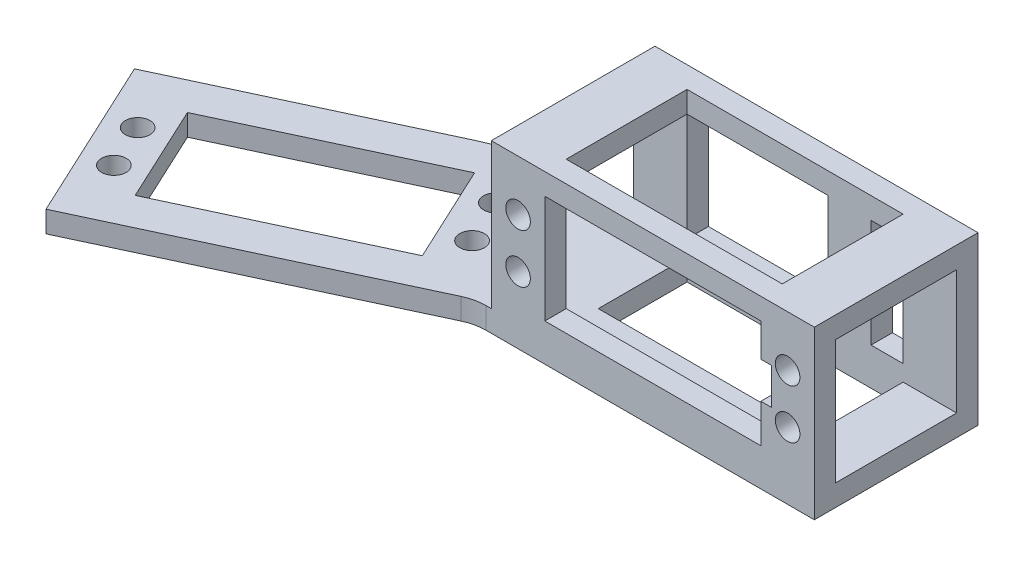
SolidWorks part; units mm, degrees
ref_plane "Płaszczyzna przednia" through (0, 0, 0) normal (0, 0, 1) x (1, 0, 0)
ref_plane "Płaszczyzna górna" through (0, 0, 0) normal (0, 1, 0) x (1, 0, 0)
ref_plane "Płaszczyzna prawa" through (0, 0, 0) normal (1, 0, 0) x (0, 0, -1)
sketch "Szkic1" plane through (0, 0, 0) normal (0, 0, 1) x (1, 0, 0)
  line L0 (17.1567, 10.1) -> (79.0535, 10.1) construction
  line L9 (-10, 27.2) -> (50.4, 27.2)
  line L10 (-10, 27.2) -> (-10, -7)
  line L11 (-10, -7) -> (50.4, -7)
  line L12 (50.4, 27.2) -> (50.4, -7)
  line L13 (20.2, 34.0981) -> (20.2, -18.6436) construction
extrude "Dodanie-wyciągnięcie1" add sketch "Szkic1" along normal blind 4
sketch "Szkic2" plane through (0, -7, 0) normal (0, -1, 0) x (1, 0, 0)
  line L1 (-10, 4) -> (-10, 0)
  line L2 (-10, 0) -> (-16.7213, 0)
  line L6 (50.4, 4) -> (50.4, 30.6)
  line L7 (50.4, 30.6) -> (-10, 30.6)
  line L9 (-10, 4) -> (50.4, 4) construction
  line L10 (-10, 4) -> (0, 4)
  line L11 (40.4, 4) -> (40.4, 20.6)
  line L12 (40.4, 20.6) -> (0, 20.6)
  line L13 (0, 20.6) -> (0, 4)
  line L14 (40.4, 4) -> (50.4, 4)
  line L16 (-38.789, 4.8923) -> (-82.1898, 25.1304)
  line L24 (50.4, 4) -> (50.4, 0) construction
  line L25 (-10, 30.6) -> (-11, 30.6)
  line L26 (-14.8036, 31.4432) -> (-67.7362, 56.1261)
  line L27 (-67.7362, 56.1261) -> (-82.1898, 25.1304)
  line L28 (-61.6315, 45.5558) -> (-70.1684, 27.2484)
  line L29 (-70.1684, 27.2484) -> (-33.5535, 10.1746)
  line L30 (-33.5535, 10.1746) -> (-25.0167, 28.482)
  line L31 (-25.0167, 28.482) -> (-61.6315, 45.5558)
  line L32 (-10, 4) -> (-10, 0) construction
  line L33 (-76.5626, 25.3669) -> (-59.3874, 62.1993) construction
  line L34 (-51.861, 18.7115) -> (-32.7873, 59.6151) construction
  line L35 (-65.8999, 36.4021) -> (-24.1196, 16.9196) construction
  arc A4 (-11, 30.6) -> (-14.8036, 31.4432) centre (-11, 39.6) cw
  arc A5 (-16.7213, 0) -> (-38.789, 4.8923) centre (-16.7213, 52.2167) cw
  circle A6 centre (-68.4874, 42.6842) radius 2.3
  circle A7 centre (-22.8095, 21.3842) radius 2.3
  circle A8 centre (-26.6976, 13.0462) radius 2.3
  circle A9 centre (-72.3755, 34.3462) radius 2.3
  point P37 (-12.9953, 30.6)
  dimension "D15" = 9
  dimension "D24" = 4.6
  dimension "D6" = 52.2167
  dimension "D1" = 10
  dimension "D2" = 10
  dimension "D3" = 10
  dimension "D4" = 26.6
  dimension "D16" = 60.4
  dimension "D17" = 7
  dimension "D18" = 7
  dimension "D19" = 40.4
  dimension "D20" = 10
  dimension "D21" = 65
  dimension "D22" = 1
  dimension "D23" = 5
  dimension "D25" = 5.5
  dimension "D26" = 20.2
extrude "Dodanie-wyciągnięcie2" add sketch "Szkic2" against normal blind 4
sketch "Szkic8" plane through (0, 0, 30.6) normal (0, 0, 1) x (1, 0, 0)
  line L0 (-9.6092, 10.1) -> (52.2876, 10.1) construction
  line L1 (0, 20.2) -> (40.4, 20.2)
  line L2 (0, 20.2) -> (0, 0)
  line L3 (0, 0) -> (40.4, 0)
  line L4 (40.4, 20.2) -> (40.4, 0)
  line L5 (-10, 25.2) -> (50.4, 25.2)
  line L6 (-10, 25.2) -> (-10, -7)
  line L7 (-10, -7) -> (50.4, -7)
  line L8 (50.4, 25.2) -> (50.4, -7)
  line L9 (20.2, 34.6544) -> (20.2, -18.0872) construction
  line L10 (50.4, -7) -> (-11, -7) construction
  line L11 (50.4, -3) -> (50.4, 27.2) construction
  circle A0 centre (-5, 14.7) radius 2.3
  circle A1 centre (-5, 5.5) radius 2.3
  circle A2 centre (45.4, 5.5) radius 2.3
  circle A3 centre (45.4, 14.7) radius 2.3
  point P29 (0, 10.1)
  point P31 (20.2, 20.2)
  dimension "D8" = 4.6
  dimension "D1" = 40.4
  dimension "D2" = 20.2
  dimension "D3" = 10
  dimension "D4" = 5
  dimension "D5" = 10
  dimension "D6" = 7
  dimension "D7" = 5.5
  dimension "D9" = 5
extrude "Dodanie-wyciągnięcie3" add sketch "Szkic8" against normal blind 4
sketch "Szkic10" plane through (0, 0, 0) normal (0, 0, -1) x (-1, 0, 0)
  line L0 (-47.6229, 10.1) -> (25.9546, 10.1) construction
  line L1 (-50.4, -7) -> (-50.4, 27.2) construction
  circle A0 centre (-30.4, 10.1) radius 1.5
  point P9 (-50.4, 10.1)
  dimension "D2" = 3
  dimension "D1" = 20
extrude "Dodanie-wyciągnięcie4" add sketch "Szkic10" along normal blind 4
sketch "Szkic11" plane through (0, 27.2, 0) normal (0, 1, 0) x (1, 0, 0)
  line L0 (50.4, -30.6) -> (-10, -30.6) construction
  line L1 (-10, 0) -> (0, 0)
  line L2 (-10, 0) -> (-10, -30.6)
  line L3 (-10, -30.6) -> (0, -30.6)
  line L4 (0, 0) -> (0, -30.6)
  line L6 (50.4, 0) -> (40.4, 0)
  line L7 (50.4, 0) -> (50.4, -30.6)
  line L8 (50.4, -30.6) -> (40.4, -30.6)
  line L9 (40.4, 0) -> (40.4, -30.6)
extrude "Dodanie-wyciągnięcie5" add sketch "Szkic11" against normal blind 5 from offset 2 offset against normal yes
sketch "Szkic12" plane through (0, 27.2, 0) normal (0, 1, 0) x (1, 0, 0)
  line L1 (-10, 0) -> (50.4, 0)
  line L2 (-10, 0) -> (-10, -4)
  line L4 (50.4, 0) -> (50.4, -4)
  line L6 (-10, -4) -> (-10, -30.6)
  line L7 (-10, -30.6) -> (50.4, -30.6)
  line L8 (50.4, -4) -> (50.4, -30.6)
extrude "Wytnij-wyciągnięcie1" cut sketch "Szkic12" against normal blind 3
sketch "Szkic13" plane through (0, 0, 0) normal (0, 0, -1) x (-1, 0, 0)
  line L0 (-40.4, 20.2) -> (0, 20.2) construction
  line L1 (-40.4, 0) -> (-40.4, 20.2) construction
  line L2 (0, 0) -> (-40.4, 0) construction
  line L3 (0, 20.2) -> (0, 0) construction
  line L4 (-40.4, 20.2) -> (-34.4, 20.2)
  line L5 (-40.4, 0) -> (-40.4, 20.2)
  line L6 (0, 0) -> (-26.4, 0)
  line L7 (0, 20.2) -> (0, 0)
  line L8 (-26.4, 20.2) -> (-26.4, 0)
  line L9 (-34.4, 20.2) -> (-34.4, 0)
  line L10 (-34.4, 0) -> (-40.4, 0)
  line L11 (-26.4, 20.2) -> (0, 20.2)
  circle A0 centre (-30.4, 10.1) radius 1.5 construction
  dimension "D1" = 4
  dimension "D2" = 4
extrude "Wytnij-wyciągnięcie2" cut sketch "Szkic13" against normal up to surface (4 mm away) up to face at (20.2, 8.6, 4)
sketch "Szkic14" plane through (0, 0, 30.6) normal (0, 0, 1) x (1, 0, 0)
  line L0 (-10, 10.6) -> (57.5346, 10.6) construction
  line L1 (-10, 24.2) -> (-10, -3) construction
  line L2 (40.4, 14) -> (42.4, 14)
  line L3 (40.4, 0) -> (40.4, 20.2) construction
  line L4 (42.4, 14) -> (42.4, 7.2)
  line L5 (40.4, 7.2) -> (42.4, 7.2)
  line L6 (40.4, 7.2) -> (40.4, 14)
  point P10 (42.4, 10.6)
  dimension "D1" = 2
  dimension "D2" = 3.4
extrude "Wytnij-wyciągnięcie3" cut sketch "Szkic14" against normal up to next
